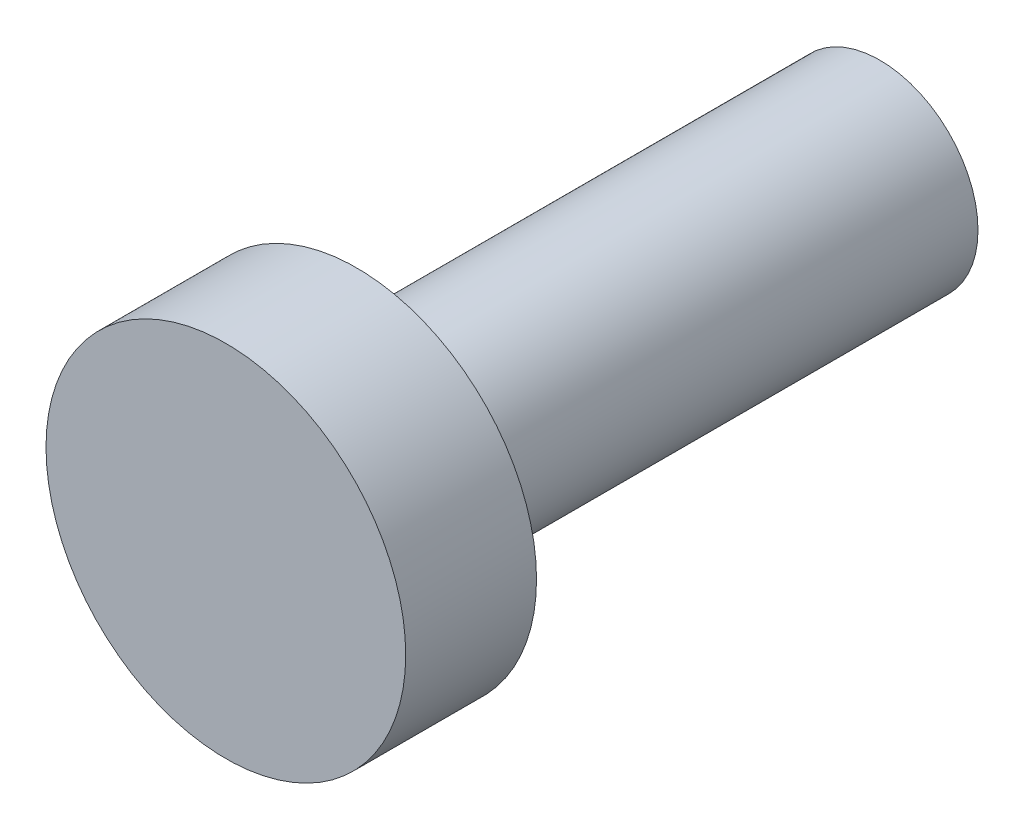
SolidWorks part; units mm, degrees
ref_plane "Front Plane" through (0, 0, 0) normal (0, 0, 1) x (1, 0, 0)
ref_plane "Top Plane" through (0, 0, 0) normal (0, 1, 0) x (1, 0, 0)
ref_plane "Right Plane" through (0, 0, 0) normal (1, 0, 0) x (0, 0, -1)
sketch "Shank_nominal_thread_envelope_profile" plane through (0, 0, 0) normal (0, 0, 1) x (1, 0, 0)
  circle A0 centre (0, 0) radius 1.5
  dimension "D1" = 3
extrude "Shank_nominal_thread_envelope" add sketch "Shank_nominal_thread_envelope_profile" along normal blind 8 from offset 8
sketch "Head_envelope_D5p5_H2p0_profile" plane through (0, 0, 0) normal (0, 0, 1) x (1, 0, 0)
  circle A0 centre (0, 0) radius 2.75
  dimension "D1" = 5.5
extrude "Head_envelope_D5p5_H2p0" add sketch "Head_envelope_D5p5_H2p0_profile" along normal blind 2
